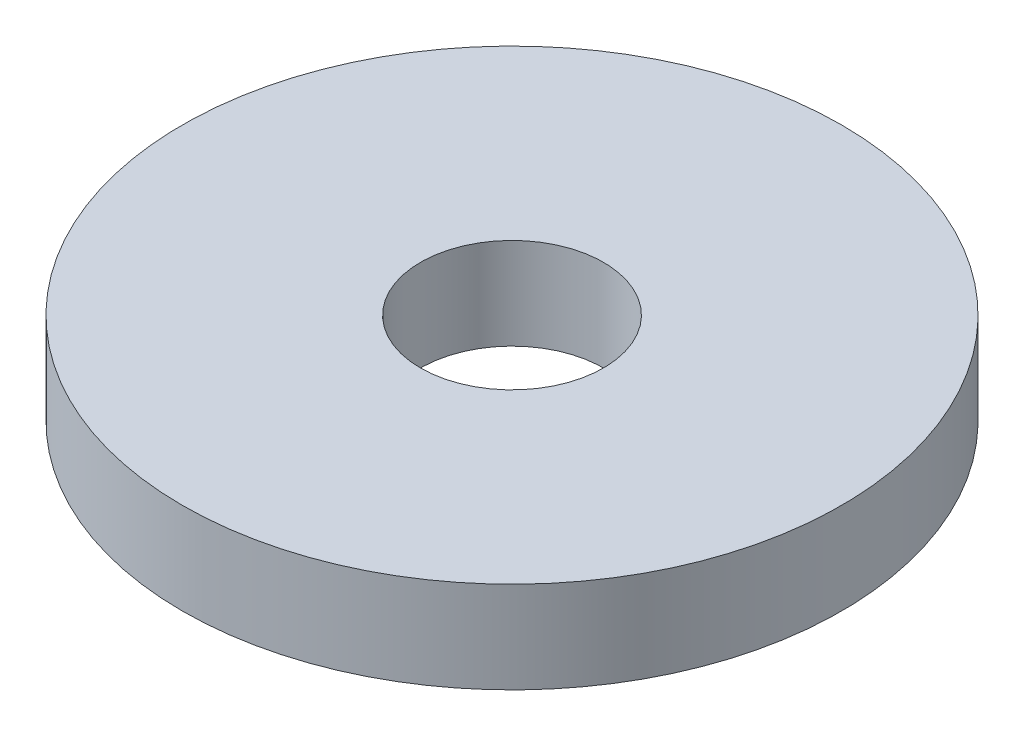
SolidWorks part; units mm, degrees
ref_plane "Front Plane" through (0, 0, 0) normal (0, 0, 1) x (1, 0, 0)
ref_plane "Top Plane" through (0, 0, 0) normal (0, 1, 0) x (1, 0, 0)
ref_plane "Right Plane" through (0, 0, 0) normal (1, 0, 0) x (0, 0, -1)
sketch "Sketch1" plane through (0, 0, 0) normal (0, 1, 0) x (1, 0, 0)
  circle A0 centre (0, 0) radius 11.43
  circle A1 centre (0, 0) radius 3.175
  dimension "D1" = 22.86
  dimension "D2" = 6.35
extrude "Boss-Extrude1" add sketch "Sketch1" along normal blind 3.175
